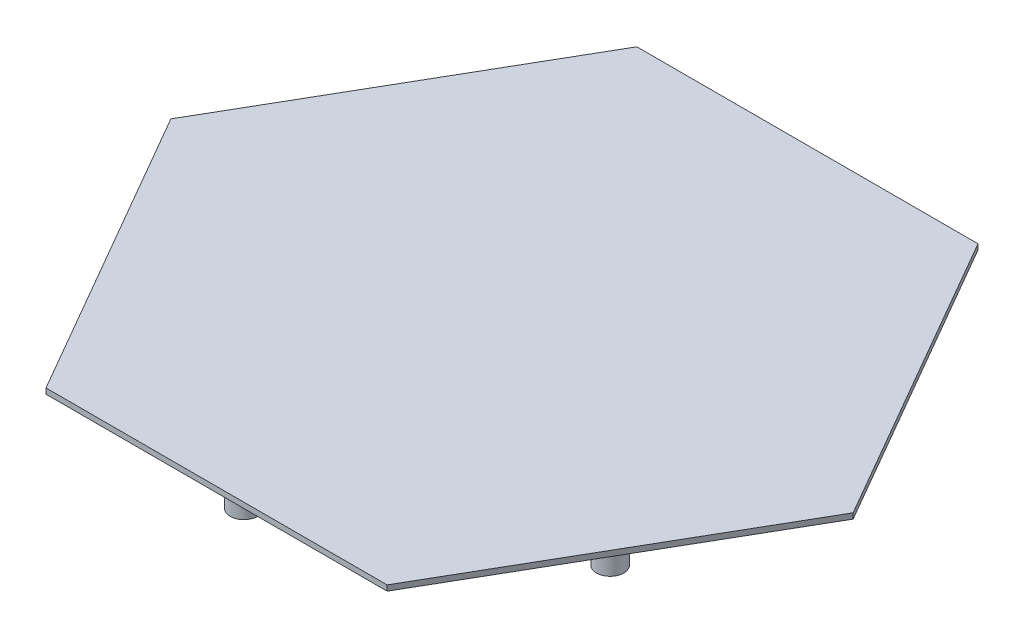
SolidWorks part; units mm, degrees
ref_plane "Front Plane" through (0, 0, 0) normal (0, 0, 1) x (1, 0, 0)
ref_plane "Top Plane" through (0, 0, 0) normal (0, 1, 0) x (1, 0, 0)
ref_plane "Right Plane" through (0, 0, 0) normal (1, 0, 0) x (0, 0, -1)
sketch "Sketch1" plane through (0, 10, 0) normal (0, 1, 0) x (1, 0, 0)
  line L0 (0, 0) -> (0, 75) construction
  circle A0 centre (0, 49) radius 2.5
  circle A1 centre (0, 0) radius 49 construction
  circle A2 centre (42.4352, 24.5) radius 2.5
  circle A3 centre (42.4352, -24.5) radius 2.5
  circle A4 centre (0, -49) radius 2.5
  circle A5 centre (-42.4352, -24.5) radius 2.5
  circle A6 centre (-42.4352, 24.5) radius 2.5
  point P20 (0, 0)
  dimension "D1" = 6
extrude "Boss-Extrude1" add sketch "Sketch1" along normal blind 5
sketch "Sketch2" plane through (0, 15, 0) normal (0, 1, 0) x (1, 0, 0)
  line L0 (66.0955, 3.5192) -> (36.0955, 55.4808) construction
  line L1 (62.3538, 0) -> (31.1769, 54)
  line L2 (31.1769, 54) -> (-31.1769, 54)
  line L3 (-31.1769, 54) -> (-62.3538, 0)
  line L4 (-62.3538, 0) -> (-31.1769, -54)
  line L5 (-31.1769, -54) -> (31.1769, -54)
  line L6 (31.1769, -54) -> (62.3538, 0)
  circle A0 centre (0, 0) radius 54 construction
  dimension "D1" = 5
extrude "Boss-Extrude2" add sketch "Sketch2" along normal blind 1
